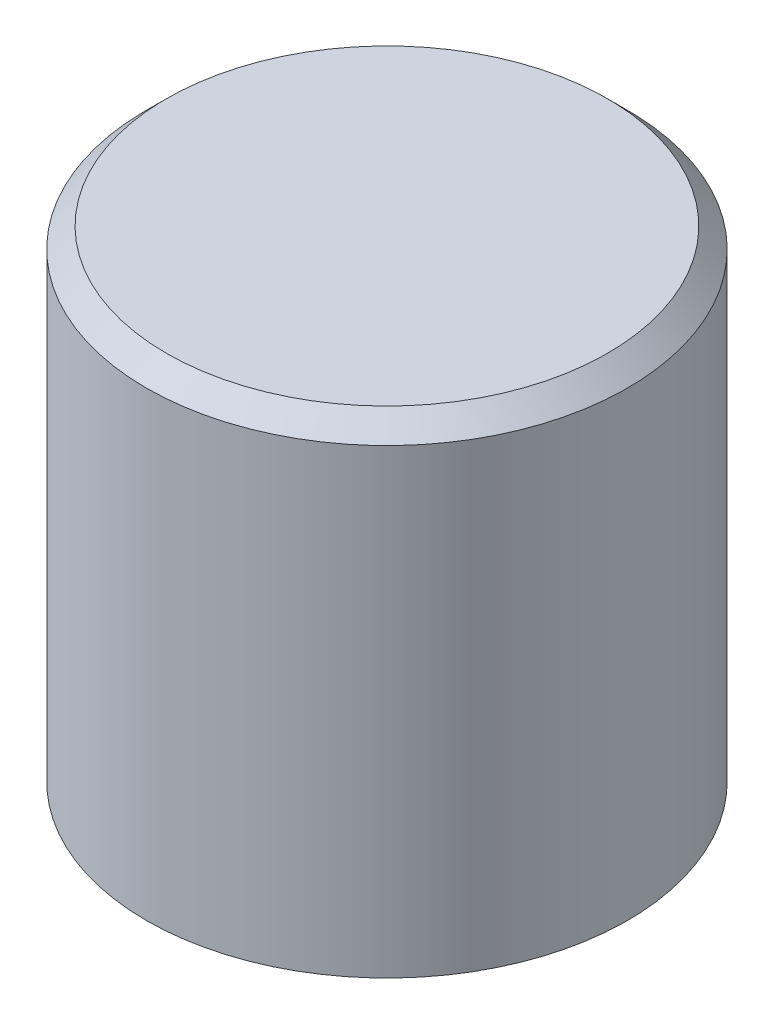
SolidWorks part; units mm, degrees
ref_plane "Front Plane" through (0, 0, 0) normal (0, 0, 1) x (1, 0, 0)
ref_plane "Top Plane" through (0, 0, 0) normal (0, 1, 0) x (1, 0, 0)
ref_plane "Right Plane" through (0, 0, 0) normal (1, 0, 0) x (0, 0, -1)
sketch "Sketch1" plane through (0, 0, 0) normal (0, 1, 0) x (1, 0, 0)
  circle A0 centre (0, 0) radius 6
  dimension "D1" = 12
extrude "Boss-Extrude1" add sketch "Sketch1" along normal blind 12
sketch "Sketch2" plane through (0, 0, 0) normal (0, 0, 1) x (1, 0, 0)
  line L0 (0, 0) -> (0, 8.5)
  line L1 (0, 8.5) -> (1.5, 8.5)
  line L2 (1.5, 8.5) -> (1.5, 3.6171)
  line L3 (1.5, 3.6171) -> (5, 3)
  line L4 (5, 3) -> (5, 0)
  line L5 (-6, 0) -> (6, 0) construction
  line L6 (5, 0) -> (0, 0)
  dimension "D1" = 8.5
  dimension "D2" = 1.5
  dimension "D3" = 3
  dimension "D4" = 5
  dimension "D5" = 80
revolve "Cut-Revolve1" cut sketch "Sketch2" angle 360 about L0
chamfer "Chamfer1" distance 0.1 angle 45 1 edges at (0, 3.6171, -1.5)
chamfer "Chamfer2" distance 0.5 angle 45 1 edges at (0, 12, 6)
